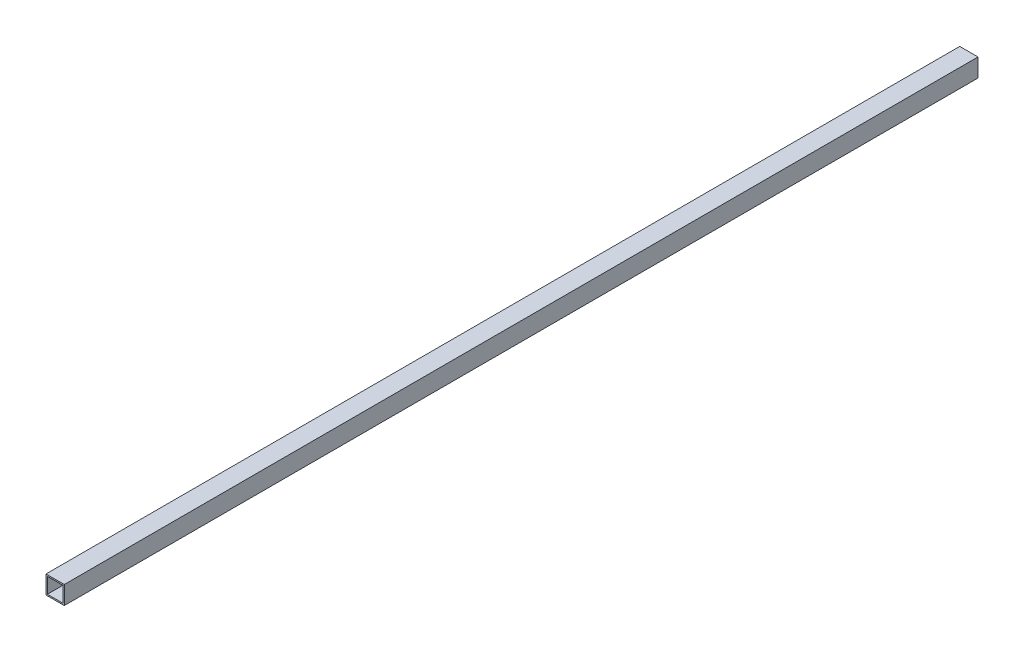
SolidWorks part; units mm, degrees
ref_plane "Front Plane" through (0, 0, 0) normal (0, 0, 1) x (1, 0, 0)
ref_plane "Top Plane" through (0, 0, 0) normal (0, 1, 0) x (1, 0, 0)
ref_plane "Right Plane" through (0, 0, 0) normal (1, 0, 0) x (0, 0, -1)
sketch "Sketch1" plane through (0, 0, 0) normal (0, 0, 1) x (1, 0, 0)
  line L1 (-20, 20) -> (20, 20)
  line L2 (-20, 20) -> (-20, -20)
  line L3 (-20, -20) -> (20, -20)
  line L4 (20, 20) -> (20, -20)
  line L5 (-20, 20) -> (20, -20) construction
  line L6 (-20, -20) -> (20, 20) construction
  point P0 (0, 0)
  dimension "D1" = 40
  dimension "D2" = 40
extrude "Boss-Extrude1" add sketch "Sketch1" along normal blind 2000
sketch "Sketch2" plane through (0, 0, 0) normal (0, 0, -1) x (-1, 0, 0)
  line L1 (-17, 17) -> (17, 17)
  line L2 (-17, 17) -> (-17, -17)
  line L3 (-17, -17) -> (17, -17)
  line L4 (17, 17) -> (17, -17)
  line L5 (-17, 17) -> (17, -17) construction
  line L6 (-17, -17) -> (17, 17) construction
  point P0 (0, 0)
  dimension "D1" = 34
  dimension "D2" = 34
extrude "Cut-Extrude1" cut sketch "Sketch2" against normal blind 2000
